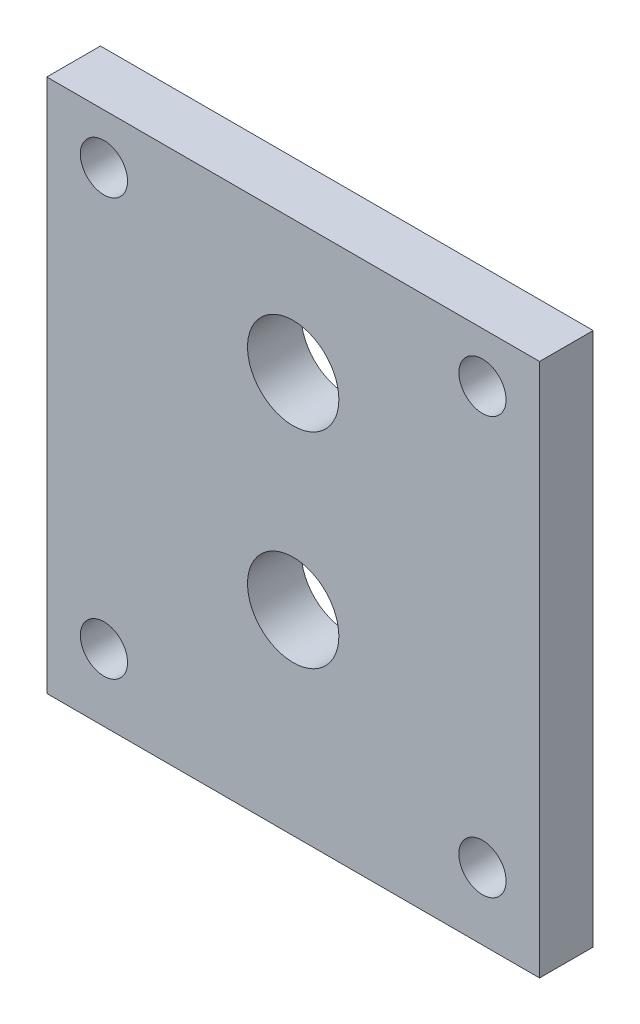
SolidWorks part; units mm, degrees
ref_plane "Front Plane" through (0, 0, 0) normal (0, 0, 1) x (1, 0, 0)
ref_plane "Top Plane" through (0, 0, 0) normal (0, 1, 0) x (1, 0, 0)
ref_plane "Right Plane" through (0, 0, 0) normal (1, 0, 0) x (0, 0, -1)
sketch "Sketch1" plane through (0, 0, 0) normal (0, 0, 1) x (1, 0, 0)
  line L0 (14.4286, -5.3597) -> (14.4286, -17.5014) construction
  line L5 (14.4286, -25.1067) -> (14.4286, -29.0838) construction
  line L8 (25.6364, -0.4229) -> (3.2209, -0.4229) construction
  line L9 (3.2209, -25.1067) -> (25.6364, -25.1067) construction
  line L10 (25.6364, -0.4229) -> (25.6364, -25.1067) construction
  line L17 (3.2209, -0.4229) -> (3.2209, -25.1067) construction
  line L19 (-0.1628, -29.0838) -> (29.02, -29.0838)
  line L20 (-0.1628, -29.0838) -> (-0.1628, 2.5359)
  line L21 (-0.1628, 2.5359) -> (29.02, 2.5359)
  line L26 (29.02, -29.0838) -> (29.02, 2.5359)
  circle A0 centre (3.2209, -0.4229) radius 1.397
  circle A1 centre (25.6364, -0.4229) radius 1.397
  circle A2 centre (25.6364, -25.1067) radius 1.397
  circle A3 centre (3.2209, -25.1067) radius 1.397
  circle A4 centre (14.4286, -5.3597) radius 2.7041
  circle A5 centre (14.4286, -17.5014) radius 2.7041
extrude "Boss-Extrude1" add sketch "Sketch1" along normal blind 3.175
